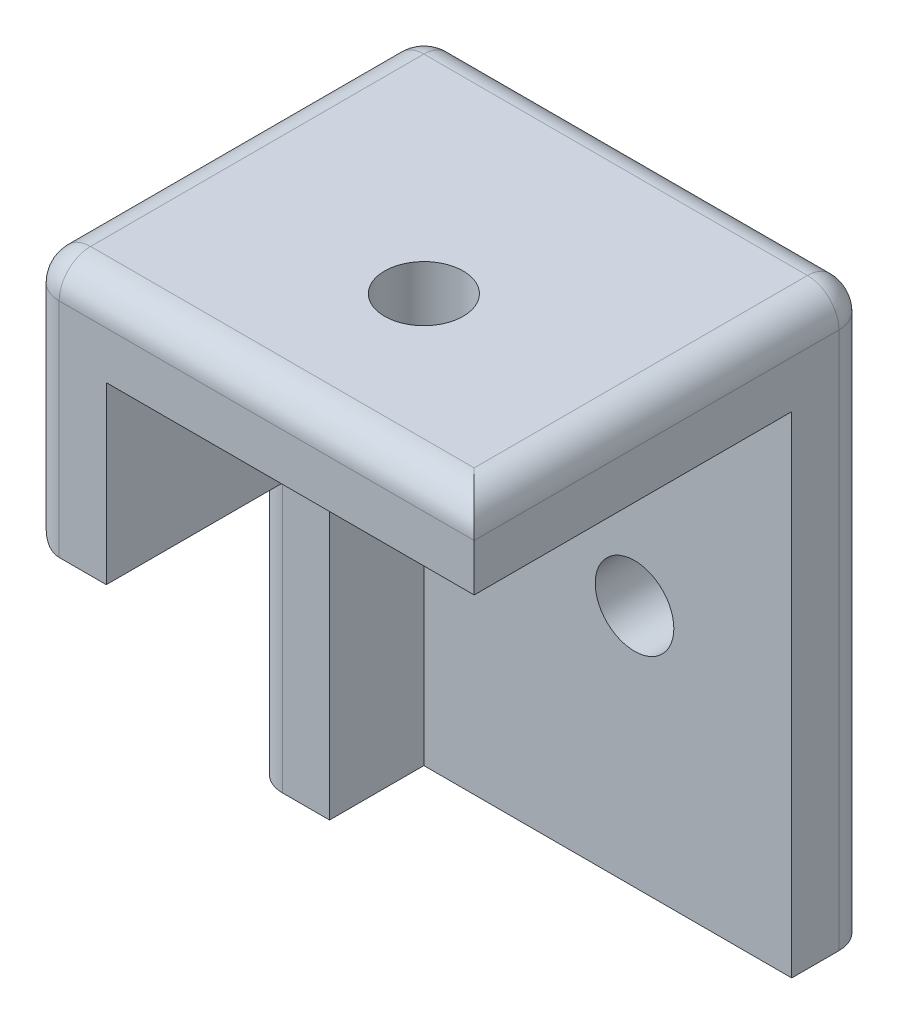
SolidWorks part; units mm, degrees
material "ABS"
ref_plane "Plan de face" through (0, 0, 0) normal (0, 0, 1) x (1, 0, 0)
ref_plane "Plan de dessus" through (0, 0, 0) normal (0, 1, 0) x (1, 0, 0)
ref_plane "Plan de droite" through (0, 0, 0) normal (1, 0, 0) x (0, 0, -1)
sketch "Esquisse1" plane through (0, 0, 0) normal (0, 0, 1) x (1, 0, 0)
  line L1 (15.8459, -68.5684) -> (39.2459, -68.5684)
  line L2 (15.8459, -68.5684) -> (15.8459, -99.7684)
  line L3 (15.8459, -99.7684) -> (39.2459, -99.7684)
  line L4 (39.2459, -68.5684) -> (39.2459, -99.7684)
  line L11 (181.0459, -68.7684) -> (16.0459, -68.7684) construction
  line L13 (181.0459, -99.7684) -> (16.0459, -99.7684) construction
  line L14 (16.0459, -96.7684) -> (16.0459, -99.7684) construction
  circle A0 centre (29.2459, -84.2684) radius 2.5
  point P4 (0, 0)
  dimension "D1" = 5
  dimension "D2" = 10
  dimension "D3" = 0.2
  dimension "D4" = 0.2
extrude "Boss.-Extru.1" add sketch "Esquisse1" along normal blind 5
sketch "Esquisse3" plane through (0, -68.5684, 0) normal (0, 1, 0) x (1, 0, 0)
  line L1 (15.8459, 0) -> (39.2459, 0)
  line L2 (15.8459, 0) -> (15.8459, -25.2)
  line L4 (39.2459, 0) -> (39.2459, -25.2)
  line L8 (15.8459, -25.2) -> (39.2459, -25.2)
  circle A0 centre (26.0459, -15.2) radius 2.5
  circle A1 centre (26.0459, -15.2) radius 2.5 construction
  dimension "D1" = 5
  dimension "D2" = 10
extrude "Boss.-Extru.3" add sketch "Esquisse3" along normal blind 5
sketch "Esquisse2" plane through (15.8459, 0, 12.4505) normal (1, 0, 0) x (0, 0, -1)
  line L5 (12.4505, -99.7684) -> (12.4505, -63.5684)
  line L6 (12.4505, -63.5684) -> (-12.7495, -63.5684)
  line L7 (-12.7495, -63.5684) -> (-12.7495, -79.7027)
  line L8 (-12.7495, -79.7027) -> (1.4505, -79.7027)
  line L9 (1.4505, -79.7027) -> (1.4505, -99.7684)
  line L11 (1.4505, -99.7684) -> (12.4505, -99.7684)
  line L12 (1.2505, -79.9027) -> (-17.1137, -79.9027) construction
  line L13 (1.2505, -94.1555) -> (1.2505, -79.9027) construction
  dimension "D1" = 0.2
  dimension "D2" = 0.2
extrude "Boss.-Extru.2" add sketch "Esquisse2" against normal blind 5
fillet "Congé1" radius 2 9 edges at (10.8459, -71.6356, 25.2) (10.8459, -79.7027, 18.1) (10.8459, -89.7356, 11) (25.0459, -63.5684, 25.2) (39.2459, -63.5684, 12.6) (39.2459, -81.6684, 0) (10.8459, -63.5684, 12.6) (25.0459, -63.5684, 0) (10.8459, -81.6684, 0)
